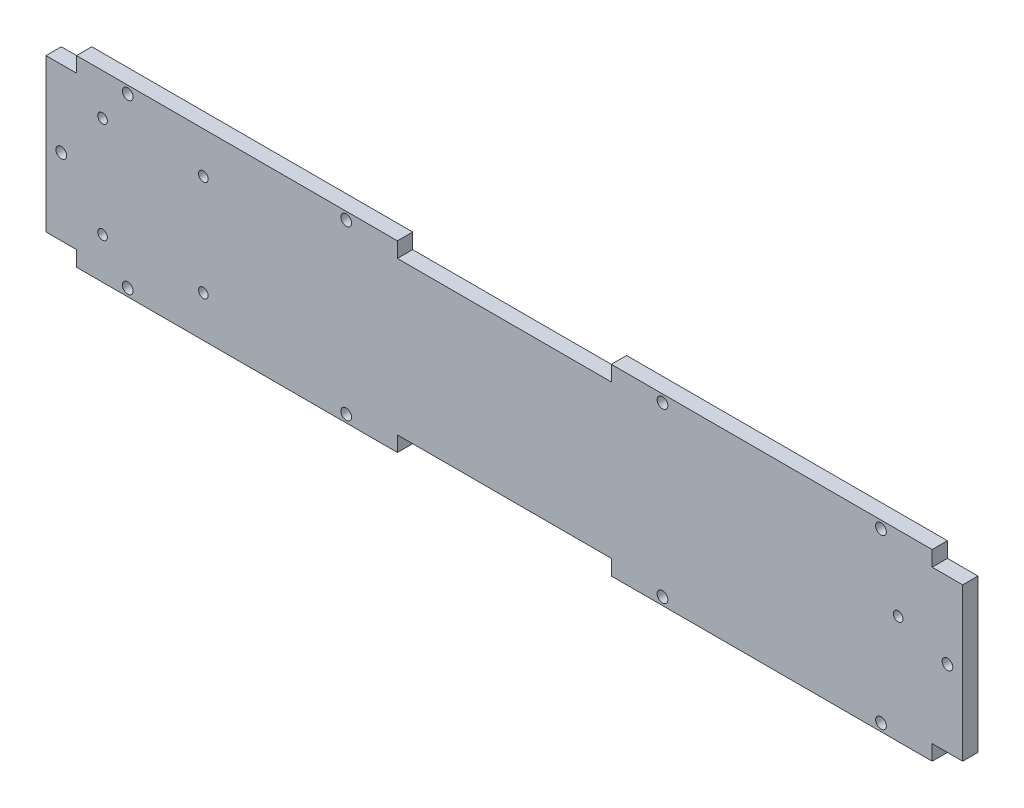
SolidWorks part; units mm, degrees
ref_plane "Front Plane" through (0, 0, 0) normal (0, 0, 1) x (1, 0, 0)
ref_plane "Top Plane" through (0, 0, 0) normal (0, 1, 0) x (1, 0, 0)
ref_plane "Right Plane" through (0, 0, 0) normal (1, 0, 0) x (0, 0, -1)
sketch "Sketch1" plane through (0, 0, 0) normal (0, 0, 1) x (1, 0, 0)
  line L0 (0, -1000) -> (0, 49000) construction
  line L1 (-140, -5) -> (-35, -5)
  line L2 (-140, -5) -> (-140, 0)
  line L3 (-140, 0) -> (-35, 0)
  line L4 (-35, -5) -> (-35, 0)
  line L5 (140, 0) -> (35, 0)
  line L6 (35, -5) -> (35, 0)
  line L7 (140, -5) -> (35, -5)
  line L8 (140, -5) -> (140, 0)
  line L9 (-1140, 25) -> (48860, 25) construction
  line L10 (-140, 0) -> (140, 0)
  line L11 (-140, 0) -> (-140, 50)
  line L12 (-140, 50) -> (140, 50)
  line L13 (140, 0) -> (140, 50)
  line L18 (140, 0) -> (150, 0)
  line L19 (140, 0) -> (140, 50)
  line L20 (140, 50) -> (140, -5)
  line L21 (140, 50) -> (150, 50)
  line L22 (-140, 0) -> (-150, 0)
  line L23 (-140, 0) -> (-140, 50)
  line L24 (-140, 50) -> (-150, 50)
  line L25 (-150, 0) -> (-150, 50)
  line L26 (150, 0) -> (150, 50)
  line L27 (140, 55) -> (140, 50)
  line L28 (140, 55) -> (35, 55)
  line L29 (35, 55) -> (35, 50)
  line L30 (140, 50) -> (35, 50)
  line L31 (-140, 50) -> (-35, 50)
  line L32 (-35, 55) -> (-35, 50)
  line L33 (-140, 55) -> (-35, 55)
  line L34 (-140, 55) -> (-140, 50)
  point P13 (0, 0)
  point P21 (-140, 25)
  dimension "D1" = 5
  dimension "D2" = 105
  dimension "D3" = 140
  dimension "D4" = 50
  dimension "D5" = 10
  dimension "D6" = 10
extrude "Boss-Extrude1" add sketch "Sketch1" along normal blind 5 contours L10 L0 L12 L11 L3 | L0 L10 L5 L13 L12 | L23 L22 L25 L24 | L19 L18 L26 L21 | L31 L32 L33 L34 | L30 L29 L28 L27
sketch "Sketch2" plane through (0, 0, 5) normal (0, 0, 1) x (1, 0, 0)
  line L0 (-87.5, -1005) -> (-87.5, 48995) construction
  line L1 (-140, -5) -> (-35, -5) construction
  line L3 (-35, -5) -> (-140, -5) construction
  line L4 (-35, -5) -> (-35, 0) construction
  line L5 (-35, 0) -> (-140, 0) construction
  line L6 (-140, -5) -> (-140, 0) construction
  line L7 (-140, -5) -> (-140, 0) construction
  line L8 (0, -1000) -> (0, 49000) construction
  line L9 (-140, -5) -> (-140, 0) construction
  line L10 (-1150, 25) -> (48850, 25) construction
  line L11 (-150, 0) -> (-150, 50) construction
  circle A0 centre (-123.25, -2.5) radius 1.75
  circle A1 centre (-51.75, -2.5) radius 1.75
  circle A2 centre (51.75, -2.5) radius 1.75
  circle A3 centre (123.25, -2.5) radius 1.75
  circle A4 centre (123.25, 52.5) radius 1.75
  circle A5 centre (51.75, 52.5) radius 1.75
  circle A6 centre (-51.75, 52.5) radius 1.75
  circle A7 centre (-123.25, 52.5) radius 1.75
  point P7 (-87.5, -5)
  point P17 (-140, -2.5)
  point P18 (-125, -2.5)
  point P33 (-150, 25)
  dimension "D1" = 3.5
  dimension "D2" = 15
extrude "Cut-Extrude1" cut sketch "Sketch2" against normal blind 5
sketch "Sketch3" plane through (0, 0, 5) normal (0, 0, 1) x (1, 0, 0)
  line L0 (-150, 0) -> (-150, 50) construction
  line L1 (0, -1000) -> (0, 49000) construction
  circle A0 centre (-145, 25) radius 1.75
  circle A1 centre (145, 25) radius 1.75
  point P5 (-150, 25)
  dimension "D1" = 3.5
  dimension "D2" = 5
extrude "Cut-Extrude2" cut sketch "Sketch3" against normal blind 10
sketch "Sketch5" plane through (0, 0, 5) normal (0, 0, 1) x (1, 0, 0)
  line L0 (-1135, 25) -> (48865, 25) construction
  line L1 (-135, 45) -> (-95, 45) construction
  line L2 (-135, 45) -> (-135, 5) construction
  line L3 (-135, 5) -> (-95, 5) construction
  line L4 (-95, 45) -> (-95, 5) construction
  line L5 (-115, -955) -> (-115, 49045) construction
  line L6 (-150, 0) -> (-150, 50) construction
  line L7 (-140, -5) -> (-35, -5) construction
  line L8 (150, 0) -> (150, 50) construction
  line L9 (140, 55) -> (35, 55) construction
  circle A0 centre (-131.5, 41.5) radius 1.575
  circle A1 centre (-98.5, 41.5) radius 1.575
  circle A2 centre (-98.5, 8.5) radius 1.575
  circle A3 centre (-131.5, 8.5) radius 1.575
  circle A4 centre (128.87, 30.5) radius 1.575
  point P9 (-135, 25)
  point P12 (-115, 45)
  dimension "D2" = 3.15
  dimension "D7" = 21.13
  dimension "D8" = 24.5
  dimension "D1" = 40
  dimension "D3" = 3.5
  dimension "D4" = 3.5
  dimension "D5" = 15
  dimension "D6" = 10
extrude "Cut-Extrude4" cut sketch "Sketch5" against normal through all
